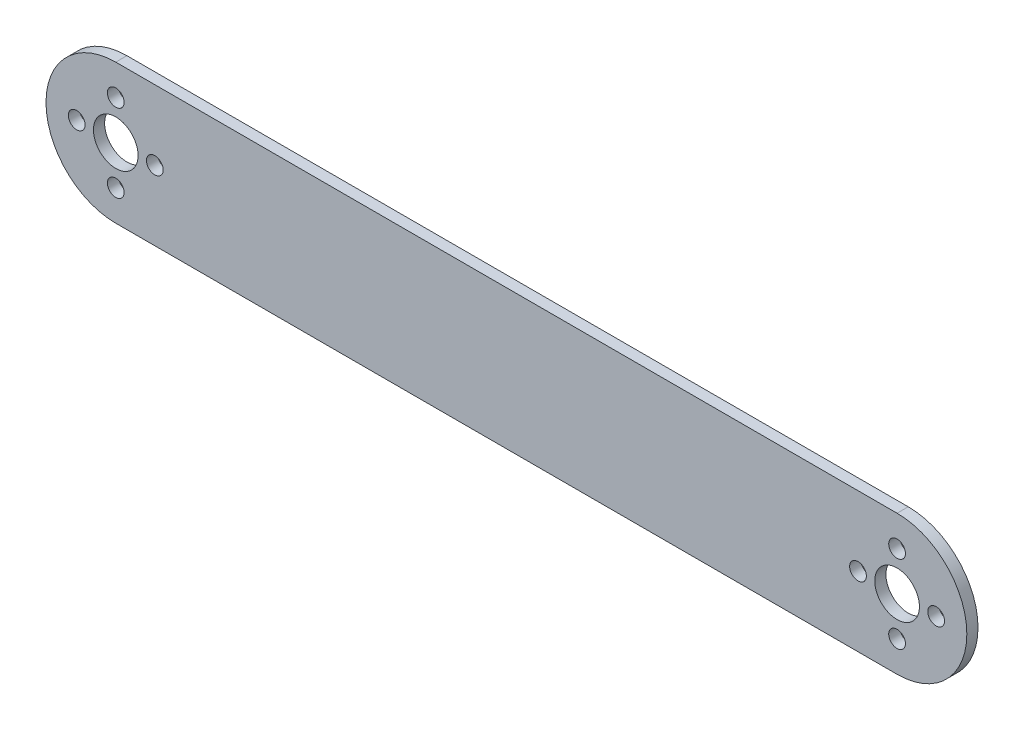
SolidWorks part; units mm, degrees
ref_plane "前视基准面" through (0, 0, 0) normal (0, 0, 1) x (1, 0, 0)
ref_plane "上视基准面" through (0, 0, 0) normal (0, 1, 0) x (1, 0, 0)
ref_plane "右视基准面" through (0, 0, 0) normal (1, 0, 0) x (0, 0, -1)
sketch "草图1" plane through (0, 0, 0) normal (0, 0, 1) x (1, 0, 0)
  line L1 (-125, -12.5) -> (15, -12.5)
  line L3 (-125, 12.5) -> (15, 12.5)
  arc A0 (15, -12.5) -> (15, 12.5) centre (15, 0) ccw
  arc A1 (-125, -12.5) -> (-125, 12.5) centre (-125, 0) cw
  circle A2 centre (15, 0) radius 4
  circle A3 centre (-125, 0) radius 4
  circle A5 centre (-125, 7) radius 1.5
  circle A7 centre (15, 7) radius 1.5
  circle A8 centre (-118, 0) radius 1.5
  circle A9 centre (-125, -7) radius 1.5
  circle A10 centre (-132, 0) radius 1.5
  circle A17 centre (22, 0) radius 1.5
  circle A18 centre (15, -7) radius 1.5
  circle A19 centre (8, 0) radius 1.5
  point P0 (0, 0)
  point P23 (-125, 0)
  point P30 (15, 0)
  point P36 (125, 0)
  dimension "D1" = 4
extrude "凸台-拉伸1" add sketch "草图1" along normal blind 2
